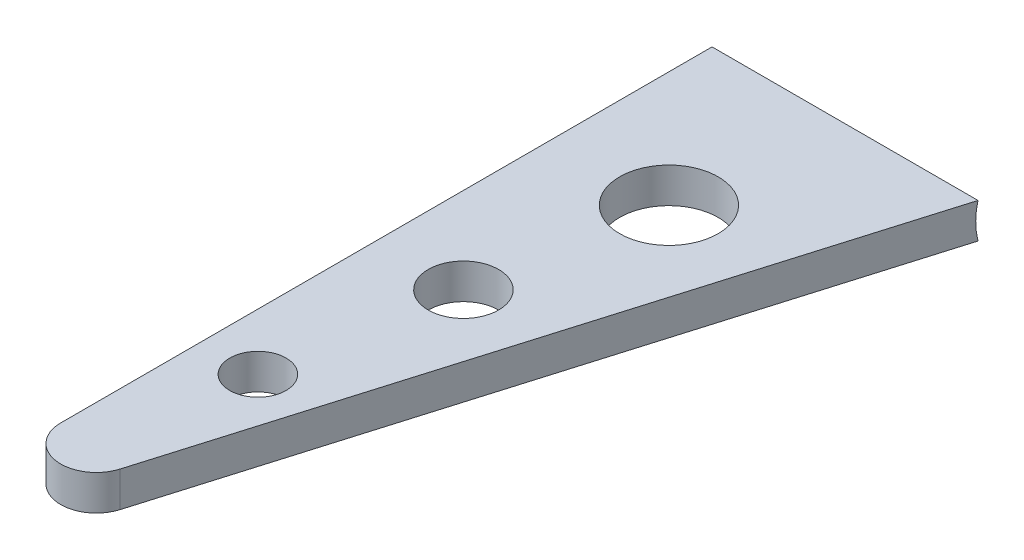
SolidWorks part; units mm, degrees
ref_plane "Front Plane" through (0, 0, 0) normal (0, 0, 1) x (1, 0, 0)
ref_plane "Top Plane" through (0, 0, 0) normal (0, 1, 0) x (1, 0, 0)
ref_plane "Right Plane" through (0, 0, 0) normal (1, 0, 0) x (0, 0, -1)
sketch "Sketch1" plane through (0, 0, 0) normal (0, 1, 0) x (1, 0, 0)
  line L0 (0, 0) -> (0, -100)
  line L2 (9.8961, -101.4375) -> (40, 0)
  line L3 (40, 0) -> (0, 0)
  line L4 (6.3177, -90.1578) -> (18.1271, -19.8422) construction
  arc A0 (0, -100) -> (9.8961, -101.4375) centre (5.0525, -100) ccw
  circle A1 centre (8.0237, -80) radius 4
  circle A2 centre (12.2224, -55) radius 5
  circle A3 centre (16.4212, -30) radius 7
  dimension "D4" = 8
  dimension "D5" = 10
  dimension "D6" = 14
  dimension "D1" = 100
  dimension "D2" = 40
  dimension "D3" = 10
  dimension "D7" = 25
  dimension "D8" = 25
  dimension "D9" = 20
extrude "Boss-Extrude1" add sketch "Sketch1" along normal blind 5
sketch "Sketch2" plane through (0, 0, 0) normal (-1, 0, 0) x (0, 0, 1)
  line L0 (0, 5) -> (0, 0) construction
  circle A0 centre (-5, 2.5) radius 12.7
  point P4 (0, 2.5)
  dimension "D1" = 25.4
  dimension "D2" = 5
extrude "Cut-Extrude1" cut sketch "Sketch2" against normal blind 50
